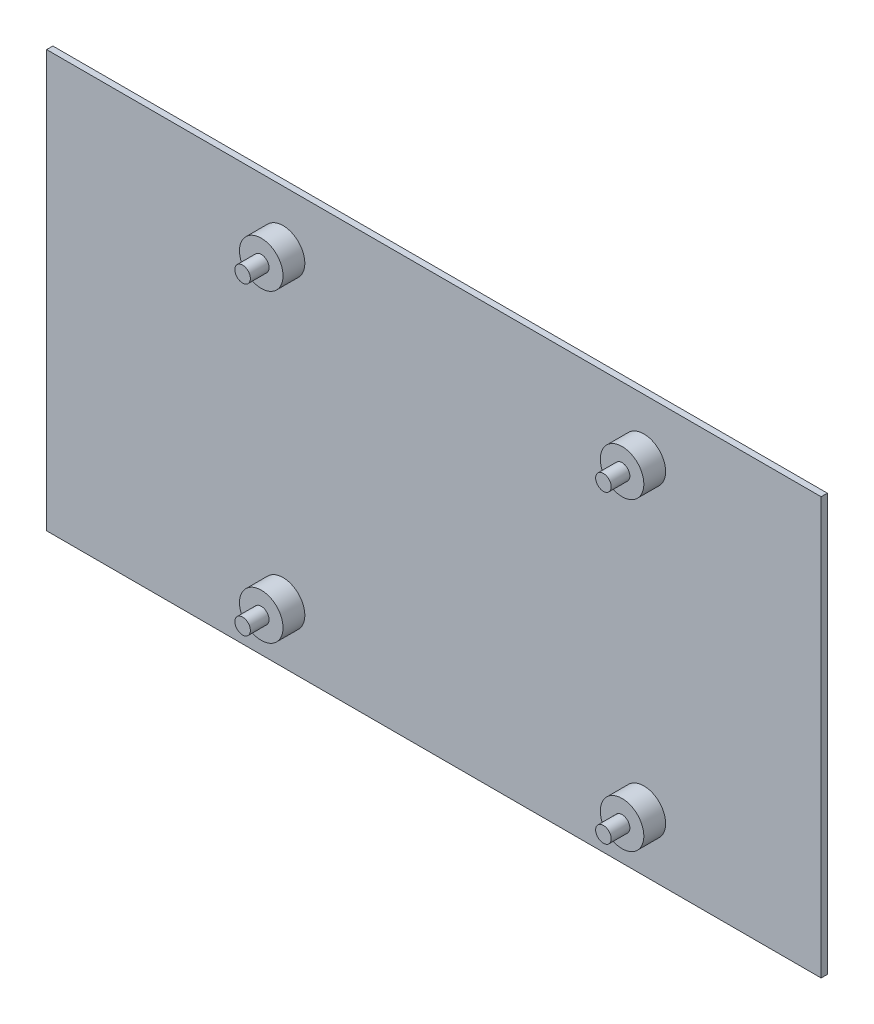
SolidWorks part; units mm, degrees
ref_plane "Front Plane" through (0, 0, 0) normal (0, 0, 1) x (1, 0, 0)
ref_plane "Top Plane" through (0, 0, 0) normal (0, 1, 0) x (1, 0, 0)
ref_plane "Right Plane" through (0, 0, 0) normal (1, 0, 0) x (0, 0, -1)
sketch "Sketch1" plane through (0, 0, 0) normal (0, 0, 1) x (1, 0, 0)
  line L1 (62.25, 33.5) -> (-62.25, 33.5)
  line L2 (62.25, 33.5) -> (62.25, -33.5)
  line L3 (62.25, -33.5) -> (-62.25, -33.5)
  line L4 (-62.25, 33.5) -> (-62.25, -33.5)
  line L5 (62.25, 33.5) -> (-62.25, -33.5) construction
  line L6 (62.25, -33.5) -> (-62.25, 33.5) construction
  point P0 (0, 0)
  dimension "D1" = 67
  dimension "D2" = 124.5
extrude "Boss-Extrude1" add sketch "Sketch1" along normal blind 1
sketch "Sketch2" plane through (0, 0, 1) normal (0, 0, 1) x (1, 0, 0)
  line L0 (4.75, 0) -> (0, 0) construction
  line L1 (33.75, 24.5) -> (-24.25, 24.5) construction
  line L2 (33.75, 24.5) -> (33.75, -24.5) construction
  line L3 (33.75, -24.5) -> (-24.25, -24.5) construction
  line L4 (-24.25, 24.5) -> (-24.25, -24.5) construction
  line L5 (33.75, 24.5) -> (-24.25, -24.5) construction
  line L6 (33.75, -24.5) -> (-24.25, 24.5) construction
  line L7 (-62.25, 33.5) -> (-62.25, -33.5) construction
  circle A0 centre (-24.25, 24.5) radius 3.5
  circle A1 centre (33.75, 24.5) radius 3.5
  circle A2 centre (33.75, -24.5) radius 3.5
  circle A3 centre (-24.25, -24.5) radius 3.5
  point P0 (4.75, 0)
  dimension "D4" = 7
  dimension "D1" = 58
  dimension "D2" = 49
  dimension "D3" = 38
extrude "Boss-Extrude2" add sketch "Sketch2" along normal blind 3.5
sketch "Sketch3" plane through (0, 0, 4.5) normal (0, 0, 1) x (1, 0, 0)
  circle A0 centre (-24.25, 24.5) radius 1.25
  circle A1 centre (33.75, 24.5) radius 1.25
  circle A2 centre (33.75, -24.5) radius 1.25
  circle A3 centre (-24.25, -24.5) radius 1.25
  dimension "D1" = 2.5
extrude "Boss-Extrude3" add sketch "Sketch3" along normal blind 3
